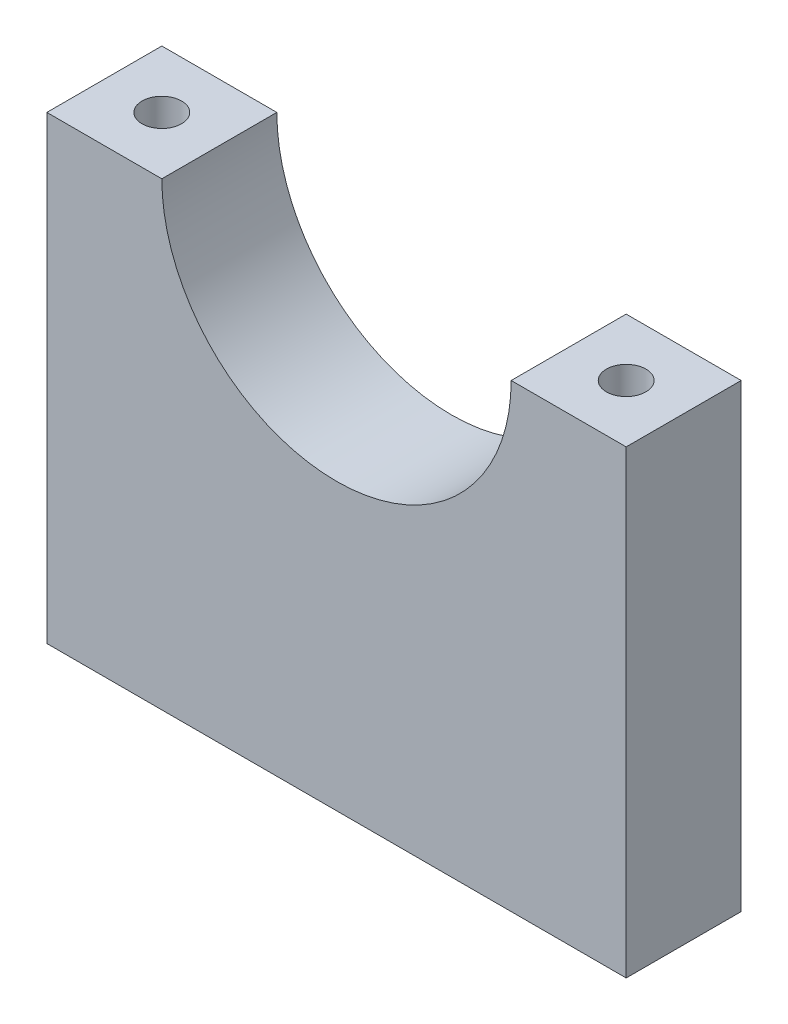
SolidWorks part; units mm, degrees
ref_plane "Front Plane" through (0, 0, 0) normal (0, 0, 1) x (1, 0, 0)
ref_plane "Top Plane" through (0, 0, 0) normal (0, 1, 0) x (1, 0, 0)
ref_plane "Right Plane" through (0, 0, 0) normal (1, 0, 0) x (0, 0, -1)
sketch "Sketch1" plane through (0, 0, 0) normal (0, 0, 1) x (1, 0, 0)
  line L0 (-31.9913, 0) -> (31.9913, 0) construction
  line L1 (-31.9913, 0) -> (-19.2913, 0)
  line L2 (-31.9913, 0) -> (31.9913, 0) construction
  line L3 (-31.9913, 0) -> (-31.9913, -50.8)
  line L4 (-31.9913, -50.8) -> (31.9913, -50.8)
  line L5 (31.9913, 0) -> (31.9913, -50.8)
  line L6 (31.9913, 0) -> (19.2913, 0)
  circle A0 centre (0, 0) radius 19.2913 construction
  arc A1 (-19.2913, 0) -> (19.2913, 0) centre (0, 0) ccw
  point P6 (0, 0)
  dimension "D1" = 38.5826
  dimension "D2" = 12.7
  dimension "D3" = 50.8
extrude "Boss-Extrude1" add sketch "Sketch1" along normal blind 12.7 contours L1 A1 L6 L5 L4 L3
sketch "Sketch2" plane through (0, -50.8, 0) normal (0, -1, 0) x (1, 0, 0)
  line L0 (-31.9913, 6.35) -> (31.9913, 6.35) construction
  line L1 (-31.9913, 12.7) -> (-31.9913, 0) construction
  line L2 (31.9913, 12.7) -> (31.9913, 0) construction
  circle A0 centre (-25.6413, 6.35) radius 2.1828
  circle A1 centre (25.6413, 6.35) radius 2.1828
  dimension "D1" = 6.35
  dimension "D2" = 6.35
extrude "Cut-Extrude1" cut sketch "Sketch2" against normal through all
